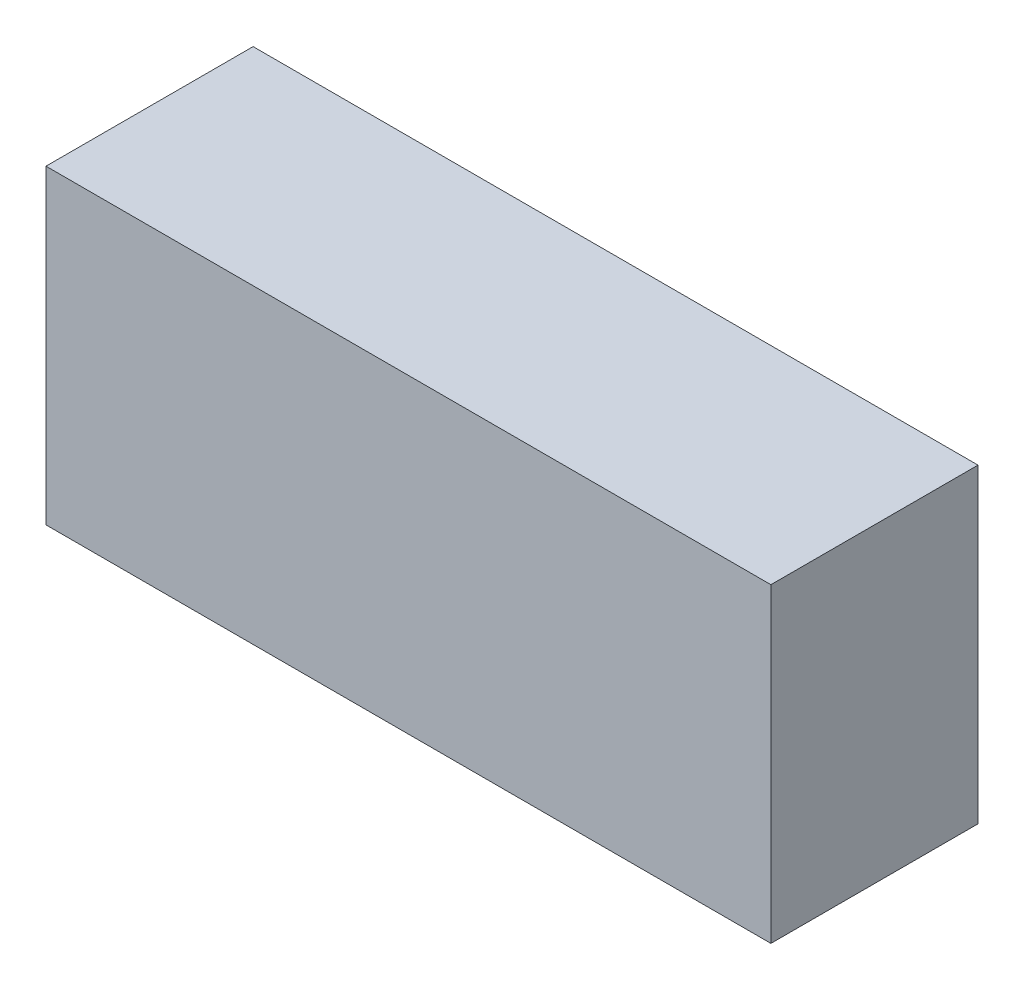
SolidWorks part; units mm, degrees
ref_plane "Front Plane" through (0, 0, 0) normal (0, 0, 1) x (1, 0, 0)
ref_plane "Top Plane" through (0, 0, 0) normal (0, 1, 0) x (1, 0, 0)
ref_plane "Right Plane" through (0, 0, 0) normal (1, 0, 0) x (0, 0, -1)
sketch "Sketch1" plane through (0, 0, 0) normal (0, 0, 1) x (1, 0, 0)
  line L2 (0, 0) -> (177.8, 0)
  line L3 (0, 0) -> (0, 76.2)
  line L4 (0, 76.2) -> (177.8, 76.2)
  line L5 (177.8, 0) -> (177.8, 76.2)
  dimension "D1" = 177.8
  dimension "D2" = 76.2
extrude "Boss-Extrude1" add sketch "Sketch1" along normal blind 50.8
